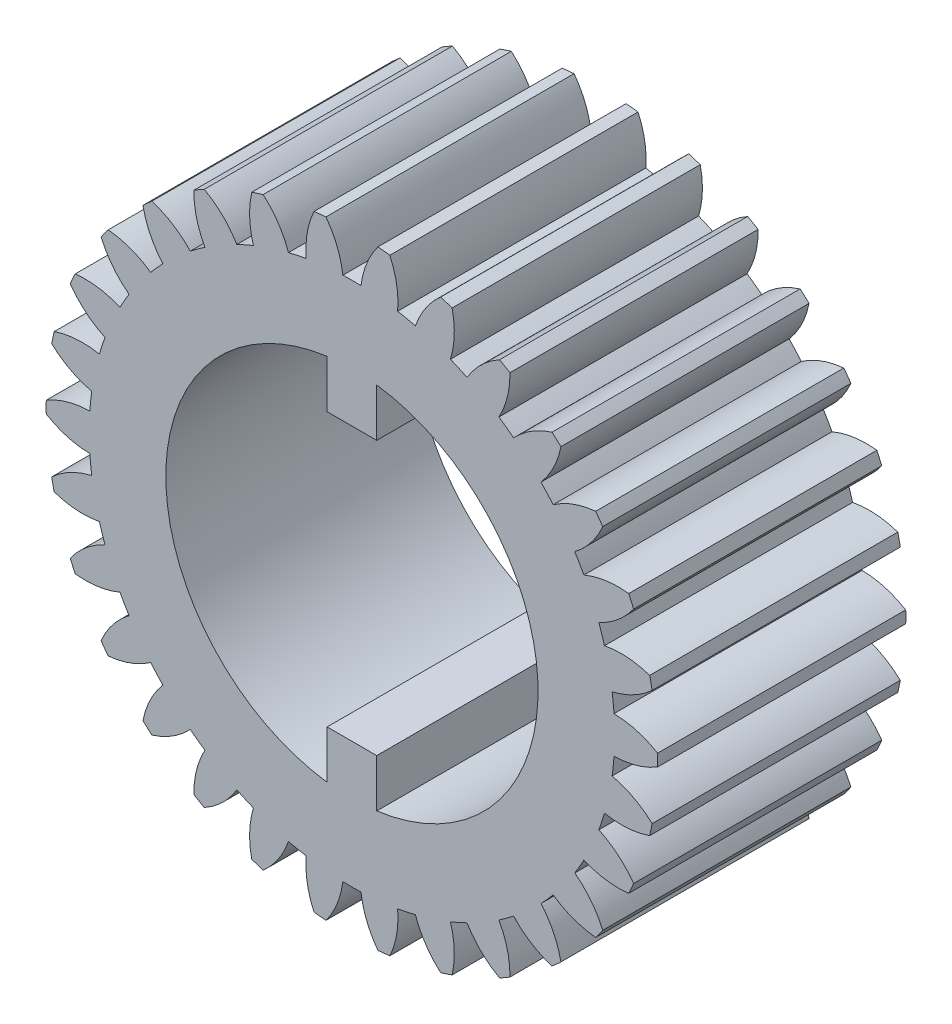
SolidWorks part; units mm, degrees
ref_plane "Front" through (0, 0, 0) normal (0, 0, 1) x (1, 0, 0)
ref_plane "Top" through (0, 0, 0) normal (0, 1, 0) x (1, 0, 0)
ref_plane "Right" through (0, 0, 0) normal (1, 0, 0) x (0, 0, -1)
sketch "Эскиз1" plane through (0, 0, 0) normal (0, 0, 1) x (1, 0, 0)
  circle A0 centre (0, 0) radius 10.5875 construction
  circle A1 centre (0, 0) radius 11.5 construction
  circle A2 centre (0, 0) radius 12.32
  circle A3 centre (0, 0) radius 10.805 construction
  dimension "D1" = 21.175
  dimension "D2" = 23
  dimension "D3" = 24.64
  dimension "D4" = 21.61
extrude "Бобышка-Вытянуть1" add sketch "Эскиз1" along normal mid plane 10
sketch "Эскиз2" plane through (0, 0, 5) normal (0, 0, 1) x (1, 0, 0)
  line L0 (-0.9448, 15.1928) -> (0, 0) construction
  line L1 (-0.7321, 11.7723) -> (-4.9391, 9.6101) construction
  line L2 (-0.6, 11.4843) -> (0.6, 11.4843) construction
  line L3 (0, 0) -> (0, 12.32) construction
  circle A0 centre (0, 0) radius 12.32 construction
  circle A1 centre (0, 0) radius 10.805 construction
  arc A2 (-1.4587, 12.7367) -> (-0.3658, 10.5812) centre (-3.8896, 10.1495) cw
  circle A3 centre (0, 0) radius 10.5875 construction
  circle A4 centre (0, 0) radius 11.5 construction
  arc A5 (1.4587, 12.7367) -> (0.3658, 10.5812) centre (3.8896, 10.1495) ccw
  arc A6 (-0.3658, 10.5812) -> (0.3658, 10.5812) centre (0, 0) cw
  circle A8 centre (0, 0) radius 12.82
  arc A9 (1.4587, 12.7367) -> (-1.4587, 12.7367) centre (0, 0) ccw
  point P3 (-0.7321, 11.7723)
  dimension "D1" = 0.525
  dimension "D2" = 1.2
  dimension "D3" = 4.7301
  dimension "D4" = 1.18
  dimension "D5" = 0.5
sketch "Эскиз4" plane through (0, 0, 0) normal (0, 1, 0) x (1, 0, 0)
  line L0 (0, 5) -> (0, -5)
  line L1 (12.32, 5) -> (-12.32, 5) construction
  line L3 (-12.32, -5) -> (12.32, -5) construction
  line L4 (0, -50) -> (0, 50) construction
  dimension "D1" = 0
curve "Кривая1"
sketch "Эскиз5" plane through (0, 0, -5) normal (0, 0, 1) x (1, 0, 0)
  line L0 (-0.9448, 15.1928) -> (0, 0) construction
  line L1 (-0.7321, 11.7723) -> (-4.9391, 9.6101) construction
  line L2 (-0.6, 11.4843) -> (0.6, 11.4843) construction
  line L3 (0, 0) -> (0, 12.32) construction
  arc A2 (-1.4587, 12.7367) -> (-0.3658, 10.5812) centre (-3.8896, 10.1495) cw
  arc A5 (1.4587, 12.7367) -> (0.3658, 10.5812) centre (3.8896, 10.1495) ccw
  arc A6 (-0.3658, 10.5812) -> (0.3658, 10.5812) centre (0, 0) cw
  arc A9 (1.4587, 12.7367) -> (-1.4587, 12.7367) centre (0, 0) ccw
  point P3 (-0.7321, 11.7723)
loft "Вырез-По сечениям1" cut profiles "Эскиз5", "Эскиз2"
pattern_circular "Круговой массив1" count 30 over 360 about axis through (0, 0, 0) along (0, 0, 1) of "Вырез-По сечениям1"
sketch "Эскиз6" plane through (0, 0, 5) normal (0, 0, 1) x (1, 0, 0)
  line L0 (0, 7.5) -> (0, -7.5) construction
  line L1 (-7.5, 0) -> (7.5, 0) construction
  line L3 (-1, 7.5) -> (1, 7.5)
  line L4 (-1, 7.5) -> (-1, 5.5)
  line L5 (-1, 5.5) -> (1, 5.5)
  line L6 (1, 7.5) -> (1, 5.5)
  line L7 (1, -7.5) -> (-1, -7.5)
  line L8 (1, -7.5) -> (1, -5.5)
  line L9 (1, -5.5) -> (-1, -5.5)
  line L10 (-1, -7.5) -> (-1, -5.5)
  circle A0 centre (0, 0) radius 7.5
  dimension "D1" = 15
  dimension "D2" = 2
  dimension "D3" = 2
extrude "Вырез-Вытянуть1" cut sketch "Эскиз6" against normal blind 10 contours L4 A0 L10 L9 L8 L6 L5
